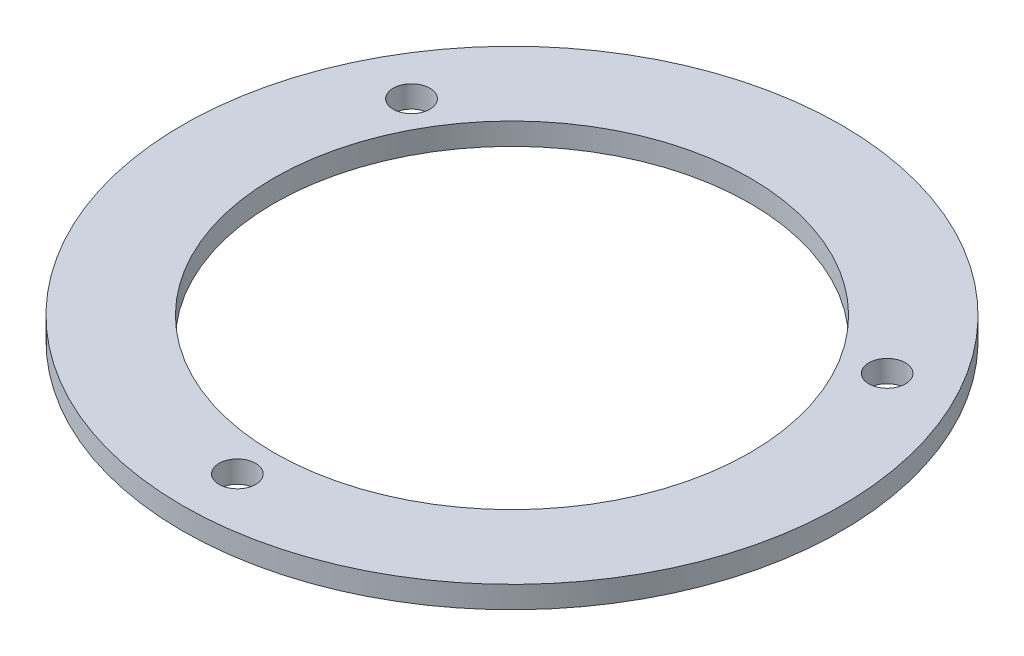
SolidWorks part; units mm, degrees
ref_plane "Front Plane" through (0, 0, 0) normal (0, 0, 1) x (1, 0, 0)
ref_plane "Top Plane" through (0, 0, 0) normal (0, 1, 0) x (1, 0, 0)
ref_plane "Right Plane" through (0, 0, 0) normal (1, 0, 0) x (0, 0, -1)
sketch "Sketch1" plane through (0, 0, 0) normal (0, 1, 0) x (1, 0, 0)
  circle A0 centre (0, 0) radius 57.15
  dimension "D1" = 114.3
extrude "Boss-Extrude1" add sketch "Sketch1" along normal blind 63.5
sketch "Sketch2" plane through (0, 63.5, 0) normal (0, 1, 0) x (1, 0, 0)
  circle A0 centre (0, 0) radius 41.275
  dimension "D1" = 82.55
extrude "Cut-Extrude1" cut sketch "Sketch2" against normal offset from surface (53.34 mm away) 10.16 up to face at (0, 0, 57.15)
sketch "Sketch3" plane through (0, 63.5, 0) normal (0, 1, 0) x (1, 0, 0)
  circle A0 centre (0, 0) radius 47.625 construction
  dimension "D1" = 95.25
hole_wizard "1/4 (0.25) Diameter Hole4" positions "Sketch5" profile "Sketch6" hole size "1/4" standard "ANSI Inch"
sketch "Sketch5" plane through (0, 63.5, 0) normal (0, 1, 0) x (1, 0, 0)
  line L0 (-41.2445, 23.8125) -> (41.2445, 23.8125) construction
  line L1 (41.2445, 23.8125) -> (0, -47.625) construction
  line L2 (0, -47.625) -> (-41.2445, 23.8125) construction
  circle A0 centre (0, 0) radius 47.625 construction
  point P0 (-41.2445, 23.8125)
  point P2 (0, -47.625)
  point P4 (41.2445, 23.8125)
  dimension "D1" = 82.4889
sketch "Sketch6" plane through (-41.2445, 63.5, -23.8125) normal (1, 0, 0) x (0, 0, 1)
  line L0 (0, 0) -> (0, 27.3077)
  line L1 (0, 27.3077) -> (3.175, 25.4)
  line L2 (3.175, 25.4) -> (3.175, 0)
  line L5 (3.175, 0) -> (0, 0)
  line L10 (0, 27.3077) -> (-3.175, 25.4) construction
  line L11 (0, -6.35) -> (0, 107.95) construction
  dimension "Hole Dia." = 6.35
  dimension "Hole Depth" = 25.4
  dimension "Drill Angle" = 118
sketch "Sketch7" plane through (0, 0, 0) normal (0, 0, 1) x (1, 0, 0)
  circle A0 centre (0, 15.24) radius 3.81
  dimension "D1" = 7.62
  dimension "D2" = 15.24
extrude "Cut-Extrude2" cut sketch "Sketch7" against normal through all
hole_wizard "Ø4.0mm Dowel Hole1" positions "3DSketch1" profile "Sketch8" hole size "Ø4.0" standard "ANSI Metric" end condition through all
sketch3d "3DSketch1"
  line L0 (-5, 0, 15.9385) -> (5, 0, -33.5615) construction
  line L2 (5, 0, 15.9385) -> (-5, 0, -33.5615) construction
  circle A0 centre (0, 0, 0) radius 57.15 construction
  point P0 (-5, 0, 15.9385)
  point P2 (5, 0, 15.9385)
  point P4 (5, 0, -33.5615)
  point P6 (-5, 0, -33.5615)
  point P29 (0, 0, -8.8115)
  point P33 (0, 57.15, 0)
  dimension "D1" = 10
  dimension "D2" = 49.5
sketch "Sketch8" plane through (-5, 0, 15.9385) normal (1, 0, 0) x (0, 0, -1)
  line L0 (0, 0) -> (0, 63.5)
  line L1 (0, 63.5) -> (2, 63.5)
  line L2 (2, 63.5) -> (2, 0)
  line L5 (2, 0) -> (0, 0)
  line L11 (0, -6.35) -> (0, 107.95) construction
  dimension "Thru Hole Dia." = 4
  dimension "Thru Hole Depth" = 63.5
sketch "Sketch9" plane through (0, 0, 0) normal (0, -1, 0) x (1, 0, 0)
  line L1 (-1.5, 12.4385) -> (-8.5, 12.4385)
  line L2 (-1.5, 12.4385) -> (-1.5, 19.4385)
  line L3 (-1.5, 19.4385) -> (-8.5, 19.4385)
  line L4 (-8.5, 12.4385) -> (-8.5, 19.4385)
  line L5 (-1.5, 12.4385) -> (-8.5, 19.4385) construction
  line L6 (-1.5, 19.4385) -> (-8.5, 12.4385) construction
  line L11 (8.5, 12.4385) -> (1.5, 12.4385)
  line L12 (8.5, 12.4385) -> (8.5, 19.4385)
  line L13 (8.5, -37.0615) -> (1.5, -37.0615)
  line L14 (8.5, -37.0615) -> (8.5, -30.0615)
  line L15 (8.5, -30.0615) -> (1.5, -30.0615)
  line L16 (1.5, -37.0615) -> (1.5, -30.0615)
  line L17 (8.5, -37.0615) -> (1.5, -30.0615) construction
  line L18 (8.5, -30.0615) -> (1.5, -37.0615) construction
  line L19 (-1.5, -37.0615) -> (-8.5, -37.0615)
  line L20 (-1.5, -37.0615) -> (-1.5, -30.0615)
  line L21 (-1.5, -30.0615) -> (-8.5, -30.0615)
  line L22 (-8.5, -37.0615) -> (-8.5, -30.0615)
  line L23 (-1.5, -37.0615) -> (-8.5, -30.0615) construction
  line L24 (-1.5, -30.0615) -> (-8.5, -37.0615) construction
  line L25 (8.5, 19.4385) -> (1.5, 19.4385)
  line L26 (1.5, 12.4385) -> (1.5, 19.4385)
  line L27 (8.5, 12.4385) -> (1.5, 19.4385) construction
  line L28 (8.5, 19.4385) -> (1.5, 12.4385) construction
  point P0 (-5, 15.9385)
  point P7 (5, 15.9385)
  point P12 (5, -33.5615)
  point P18 (-5, -33.5615)
  dimension "D1" = 7
  dimension "D2" = 7
extrude "Cut-Extrude3" cut sketch "Sketch9" against normal blind 3.5
ref_plane "Plane1" through (0, 50.8, 0) normal (0, 1, 0) x (1, 0, 0)
sketch "Sketch12" plane through (0, 50.8, 0) normal (0, 1, 0) x (1, 0, 0)
  line L1 (-38.4946, 14.8925) -> (-32.1446, 25.8911)
  line L3 (-48.6424, 35.4161) -> (-54.9924, 24.4175)
  line L5 (48.6424, 35.4161) -> (54.9924, 24.4175)
  line L7 (38.4946, 14.8925) -> (32.1446, 25.8911)
  line L8 (-48.6424, 35.4161) -> (-32.1446, 25.8911)
  line L13 (6.35, -59.8336) -> (-6.35, -59.8336)
  line L14 (6.35, -59.8336) -> (6.35, -40.7836)
  line L15 (6.35, -40.7836) -> (-6.35, -40.7836)
  line L16 (-6.35, -59.8336) -> (-6.35, -40.7836)
  line L19 (-54.9924, 24.4175) -> (-38.4946, 14.8925)
  line L20 (48.6424, 35.4161) -> (32.1446, 25.8911)
  line L21 (54.9924, 24.4175) -> (38.4946, 14.8925)
  line L22 (0, 0) -> (51.8174, 29.9168) construction
  line L23 (0, 0) -> (-51.8174, 29.9168)
  circle A1 centre (0, 0) radius 41.275 construction
  circle A2 centre (0, 0) radius 41.275 construction
  point P14 (0, -47.625)
  point P15 (0, -47.625)
  dimension "D1" = 12.7
  dimension "D2" = 19.05
extrude "Cut-Extrude4" cut sketch "Sketch12" along normal blind 4.7625 contours L1 L23 L3 L19 | L23 L1 L8 L3 | L7 L22 L5 L20 | L22 L7 L21 L5 | L16 L13 L14 L15
sketch "Sketch13" plane through (0, 0, 0) normal (0, -1, 0) x (1, 0, 0)
  circle A0 centre (0, 0) radius 64.7946
extrude "Cut-Extrude5" cut sketch "Sketch13" against normal offset from surface (59.69 mm away) 3.81 up to face at (-41.2445, 63.5, -20.6375)
